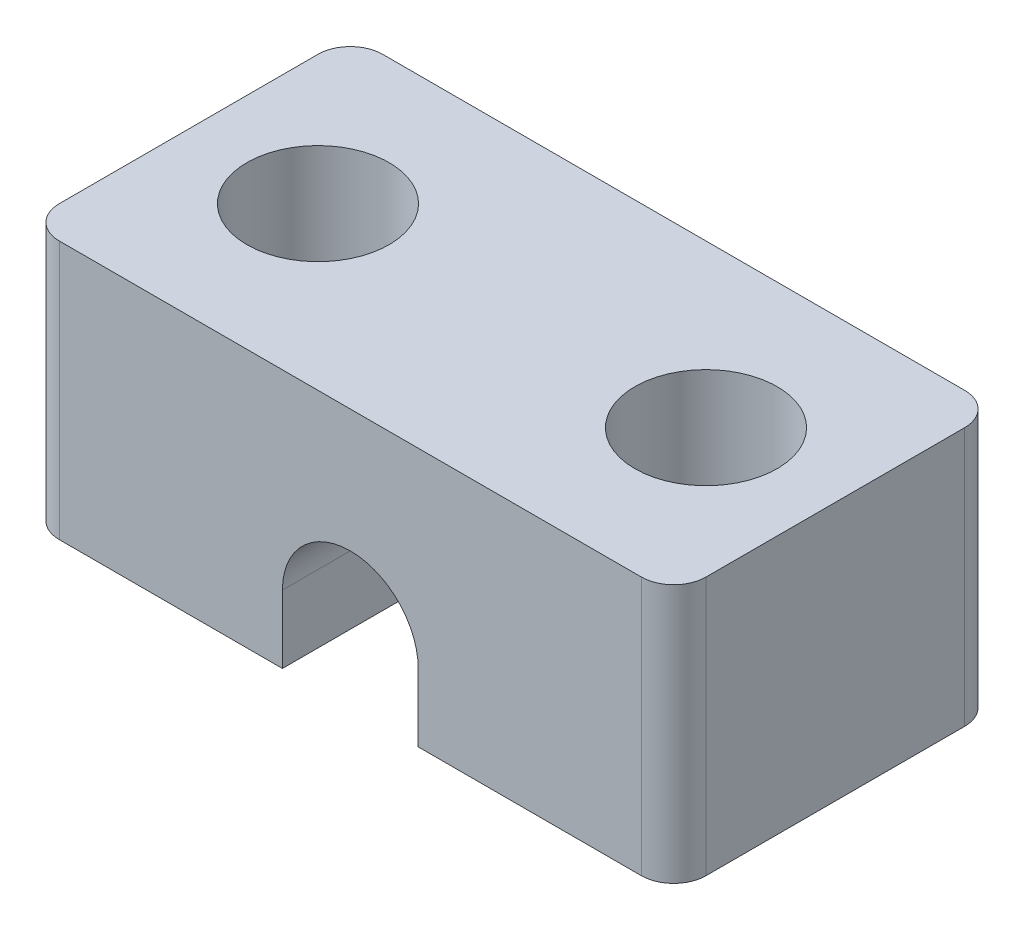
SolidWorks part; units mm, degrees
material "ABS"
ref_plane "前视基准面" through (0, 0, 0) normal (0, 0, 1) x (1, 0, 0)
ref_plane "上视基准面" through (0, 0, 0) normal (0, 1, 0) x (1, 0, 0)
ref_plane "右视基准面" through (0, 0, 0) normal (1, 0, 0) x (0, 0, -1)
sketch "草图1" plane through (0, 0, 0) normal (0, 0, 1) x (1, 0, 0)
  line L0 (2.1, -2.1) -> (10, -2.1)
  line L1 (-10, 5.9) -> (10, 5.9)
  line L2 (-10, 5.9) -> (-10, -2.1)
  line L3 (-10, -2.1) -> (-2.1, -2.1)
  line L4 (10, 5.9) -> (10, -2.1)
  line L6 (-2.1, 0) -> (-2.1, -2.1)
  line L8 (2.1, 0) -> (2.1, -2.1)
  arc A0 (2.1, 0) -> (-2.1, 0) centre (0, 0) ccw
  dimension "D1" = 2.1
  dimension "D2" = 20
  dimension "D3" = 7.9
  dimension "D4" = 8
extrude "凸台-拉伸1" add sketch "草图1" along normal mid plane 10
sketch "草图2" plane through (0, 5.9, 0) normal (0, 1, 0) x (1, 0, 0)
  line L0 (-6, 0) -> (6, 0) construction
  line L1 (-10, -5) -> (-10, 5) construction
  circle A0 centre (-6, 0) radius 2.2
  circle A1 centre (6, 0) radius 2.2
  dimension "D2" = 4.4
  dimension "D1" = 4
extrude "切除-拉伸1" cut sketch "草图2" against normal through all
sketch "草图3" plane through (0, 0, -5) normal (0, 0, -1) x (-1, 0, 0)
  line L0 (2.1, -2.1) -> (2.1, 0) construction
  line L1 (-2.1, -2.1) -> (-10, -2.1) construction
  line L2 (-2.1, 0) -> (-2.1, -2.1) construction
  line L3 (2.1, -2.1) -> (2.1, 0)
  line L4 (-2.1, -2.1) -> (2.1, -2.1)
  line L5 (-2.1, 0) -> (-2.1, -2.1)
  arc A0 (2.1, 0) -> (-2.1, 0) centre (0, 0) ccw construction
  arc A1 (2.1, 0) -> (-2.1, 0) centre (0, 0) ccw
extrude "凸台-拉伸2" add sketch "草图3" against normal blind 5.8
fillet "圆角1" radius 1 4 edges at (10, 1.9, -5) (10, 1.9, 5) (-10, 1.9, -5) (-10, 1.9, 5)
